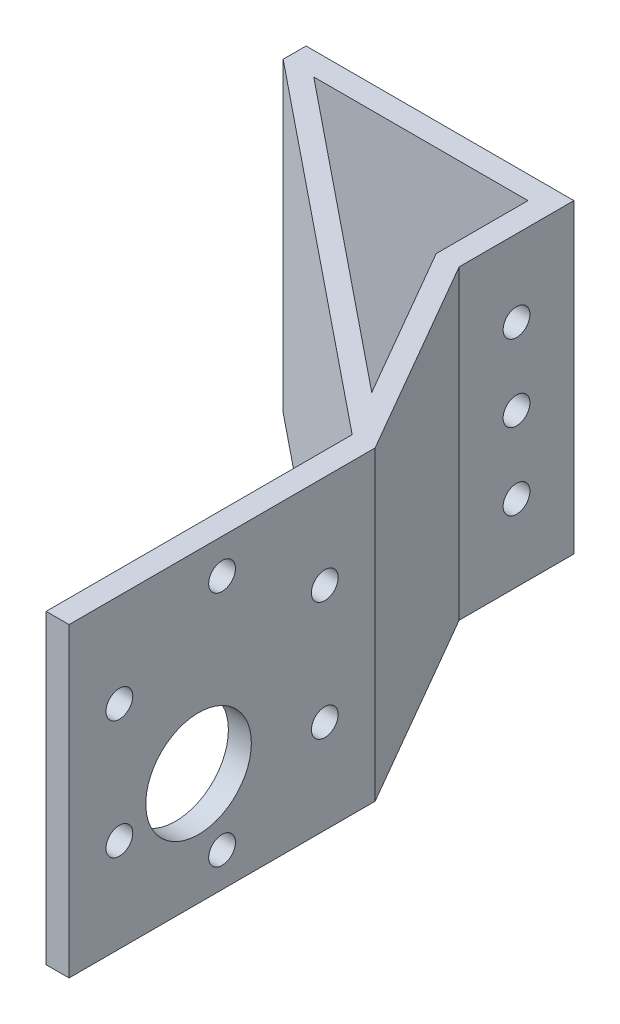
SolidWorks part; units mm, degrees
ref_plane "Ön Düzlem" through (0, 0, 0) normal (0, 0, 1) x (1, 0, 0)
ref_plane "Üst Düzlem" through (0, 0, 0) normal (0, 1, 0) x (1, 0, 0)
ref_plane "Sağ Düzlem" through (0, 0, 0) normal (1, 0, 0) x (0, 0, -1)
sketch "Çizim1" plane through (0, 0, 0) normal (0, 1, 0) x (1, 0, 0)
  line L0 (0, 0) -> (-35, 0)
  line L1 (0, 0) -> (0, -15)
  line L2 (0, -15) -> (15, -40.9808)
  line L3 (-35, 0) -> (-35, -3)
  line L5 (15, -40.9808) -> (15, -80.9808)
  line L7 (-3, -15) -> (-3, -3)
  line L8 (-3, -3) -> (-31, -3)
  line L10 (-3, -15) -> (8.5015, -34.9212)
  line L11 (12, -40.9808) -> (12, -80.9808)
  line L12 (12, -80.9808) -> (15, -80.9808)
  line L13 (-35, -3) -> (12, -40.9808)
  line L15 (-31, -3) -> (8.5015, -34.9212)
  dimension "D1" = 150
  dimension "D2" = 30
  dimension "D3" = 2.5981
extrude "Yükseklik-Ekstrüzyon1" add sketch "Çizim1" along normal blind 40
sketch "Çizim2" plane through (0, 0, 0) normal (1, 0, 0) x (0, 0, -1)
  point P9 (-7.5, 20)
sketch "Çizim3" plane through (0, 0, 0) normal (1, 0, 0) x (0, 0, -1)
  circle A3 centre (-7.5, 20) radius 1.75
  circle A5 centre (-7.5, 30) radius 1.75
  circle A6 centre (-7.5, 10) radius 1.75
extrude "Kes-Ekstrüzyon2" cut sketch "Çizim3" against normal blind 3
sketch "Çizim4" plane through (15, 0, 0) normal (1, 0, 0) x (0, 0, -1)
  circle A2 centre (-60.9808, 35.5) radius 1.75
  circle A3 centre (-47.5574, 27.75) radius 1.75
  circle A4 centre (-47.5574, 12.25) radius 1.75
  circle A5 centre (-60.9808, 4.5) radius 1.75
  circle A6 centre (-74.4042, 12.25) radius 1.75
  circle A7 centre (-74.4042, 27.75) radius 1.75
  circle A8 centre (-64.0549, 14.6754) radius 6.8983
extrude "Kes-Ekstrüzyon3" cut sketch "Çizim4" against normal blind 37
